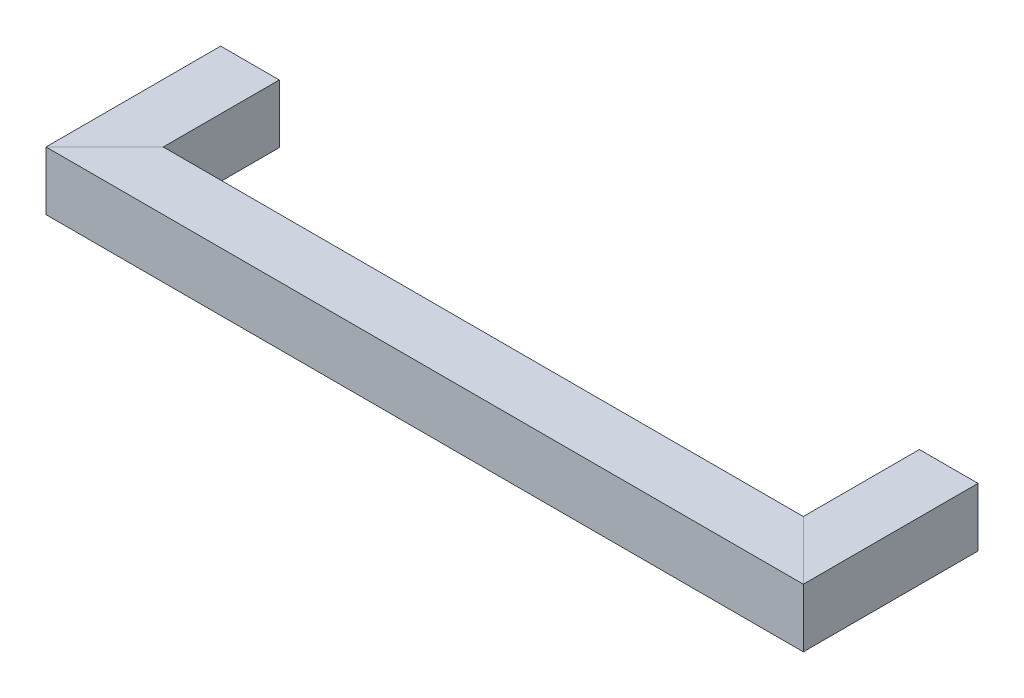
SolidWorks part; units mm, degrees
ref_plane "Front Plane" through (0, 0, 0) normal (0, 0, 1) x (1, 0, 0)
ref_plane "Top Plane" through (0, 0, 0) normal (0, 1, 0) x (1, 0, 0)
ref_plane "Right Plane" through (0, 0, 0) normal (1, 0, 0) x (0, 0, -1)
sketch "Sketch1" plane through (0, 0, 0) normal (0, 0, 1) x (1, 0, 0)
  line L1 (12.5, -12.5) -> (-12.5, -12.5)
  line L2 (12.5, -12.5) -> (12.5, 12.5)
  line L3 (12.5, 12.5) -> (-12.5, 12.5)
  line L4 (-12.5, -12.5) -> (-12.5, 12.5)
  line L5 (12.5, -12.5) -> (-12.5, 12.5) construction
  line L6 (12.5, 12.5) -> (-12.5, -12.5) construction
  point P0 (0, 0)
  dimension "D1" = 25
  dimension "D2" = 25
sketch "Sketch2" plane through (0, 0, 0) normal (0, 1, 0) x (1, 0, 0)
  line L0 (0, 0) -> (0, -62)
  line L1 (0, -62) -> (298, -62)
  line L2 (298, -62) -> (298, 0)
  dimension "D1" = 62
  dimension "D2" = 298
  dimension "D3" = 62
sweep "Sweep1" add profiles "Sketch1" path "Sketch2"
